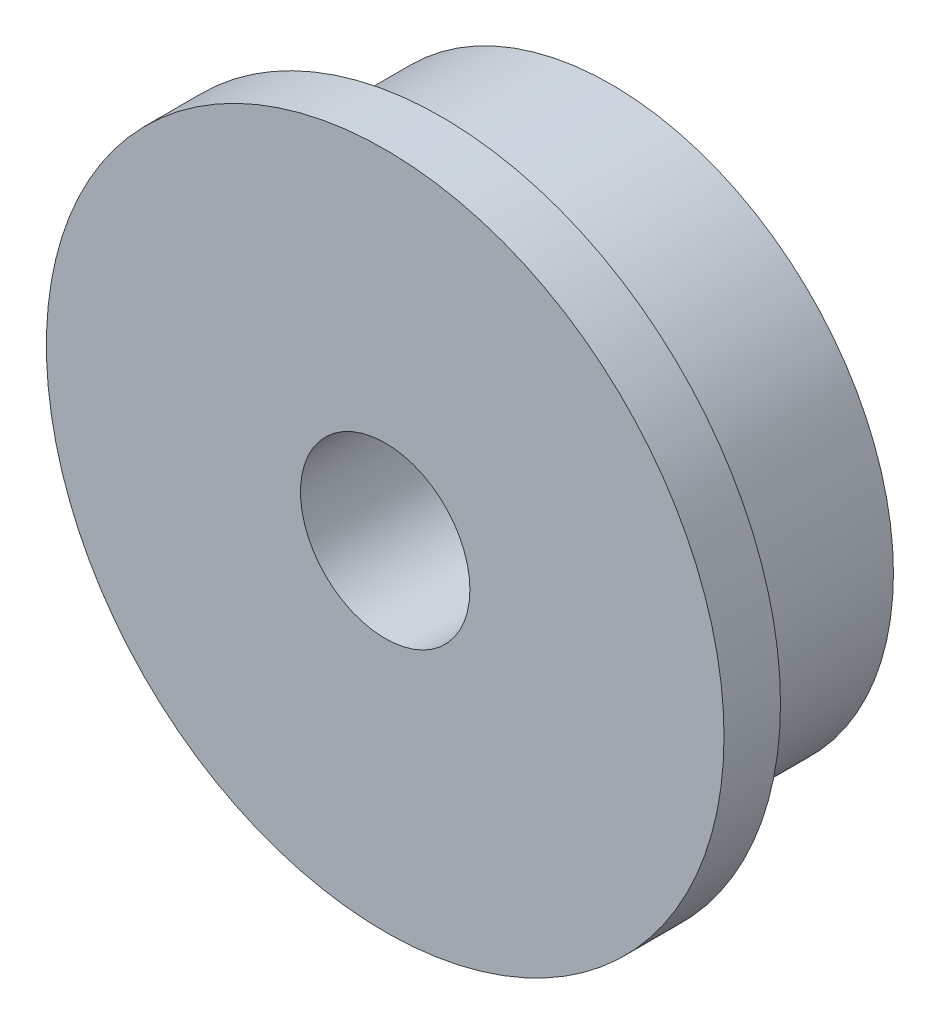
SolidWorks part; units mm, degrees
ref_plane "Спереди" through (0, 0, 0) normal (0, 0, 1) x (1, 0, 0)
ref_plane "Сверху" through (0, 0, 0) normal (0, 1, 0) x (1, 0, 0)
ref_plane "Справа" through (0, 0, 0) normal (1, 0, 0) x (0, 0, -1)
sketch "Эскиз1" plane through (0, 0, 0) normal (0, 0, 1) x (1, 0, 0)
  circle A0 centre (0, 0) radius 1.5
  circle A1 centre (0, 0) radius 5
extrude "Бобышка-Вытянуть1" add sketch "Эскиз1" along normal blind 4
sketch "Эскиз2" plane through (0, 0, 4) normal (0, 0, 1) x (1, 0, 0)
  circle A0 centre (0, 0) radius 5
  circle A1 centre (0, 0) radius 6
extrude "Бобышка-Вытянуть2" add sketch "Эскиз2" against normal blind 1
